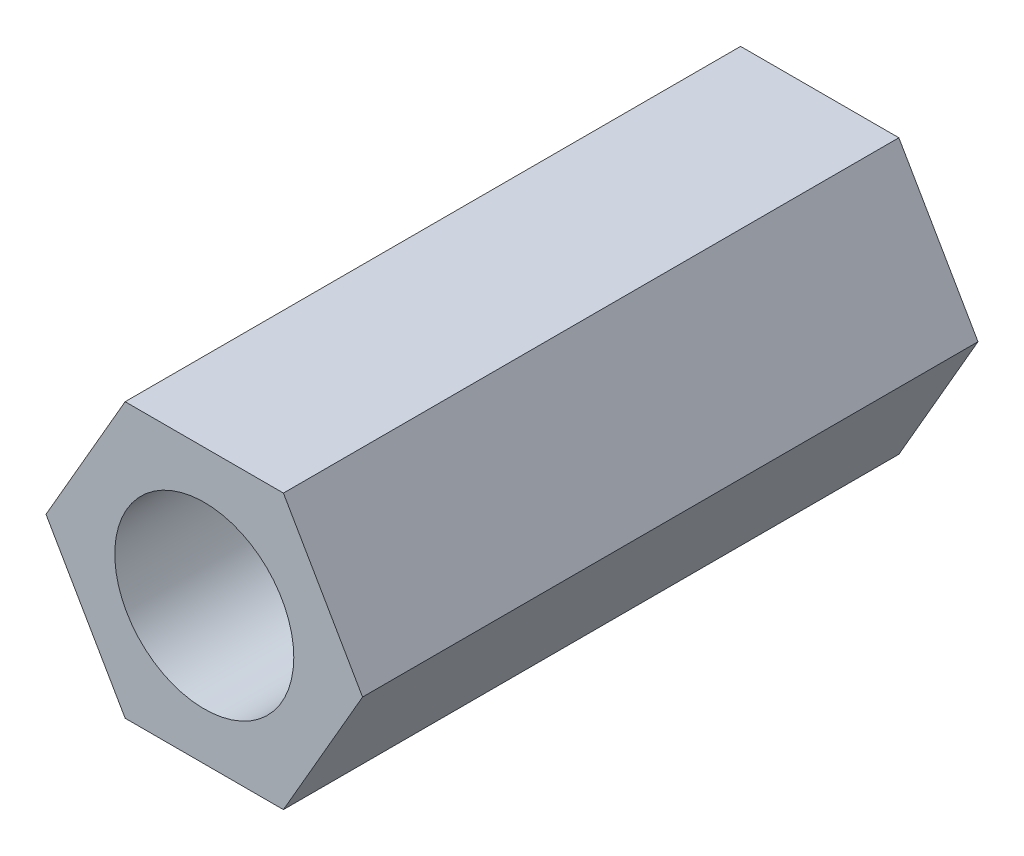
SolidWorks part; units mm, degrees
material "黄铜"
ref_plane "前视基准面" through (0, 0, 0) normal (0, 0, 1) x (1, 0, 0)
ref_plane "上视基准面" through (0, 0, 0) normal (0, 1, 0) x (1, 0, 0)
ref_plane "右视基准面" through (0, 0, 0) normal (1, 0, 0) x (0, 0, -1)
sketch "草图1" plane through (0, 0, 0) normal (0, 0, 1) x (1, 0, 0)
  line L1 (2.829, 0) -> (1.4145, 2.45)
  line L2 (1.4145, 2.45) -> (-1.4145, 2.45)
  line L3 (-1.4145, 2.45) -> (-2.829, 0)
  line L4 (-2.829, 0) -> (-1.4145, -2.45)
  line L5 (-1.4145, -2.45) -> (1.4145, -2.45)
  line L6 (1.4145, -2.45) -> (2.829, 0)
  circle A0 centre (0, 0) radius 1.6
  circle A1 centre (0, 0) radius 2.45 construction
  dimension "D1" = 3.2
  dimension "D2" = 4.9
extrude "凸台-拉伸1" add sketch "草图1" along normal blind 11
